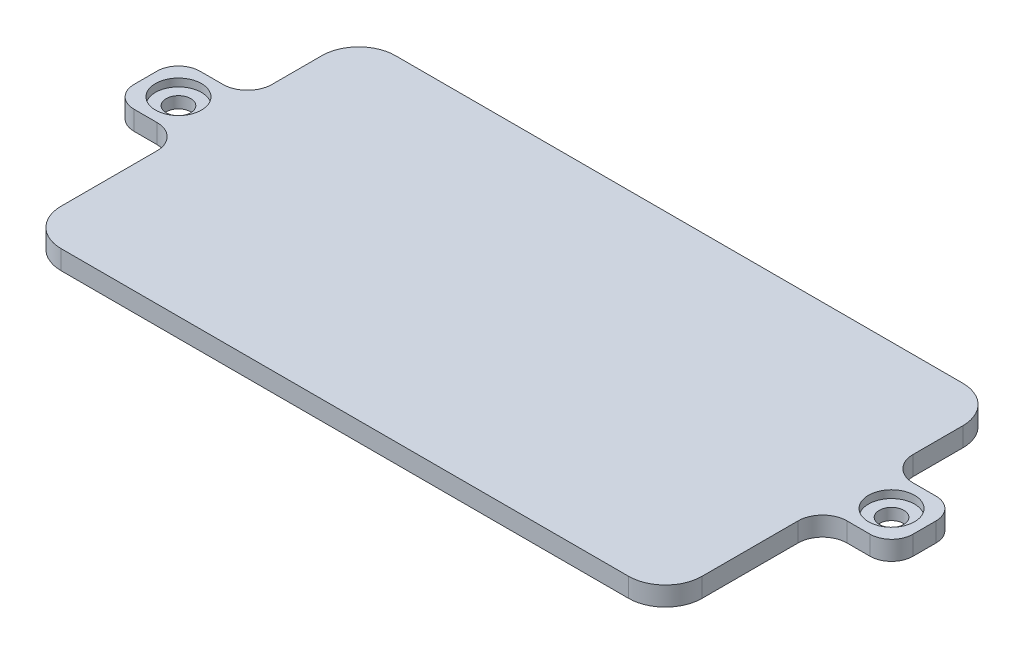
SolidWorks part; units mm, degrees
ref_plane "Front Plane" through (0, 0, 0) normal (0, 0, 1) x (1, 0, 0)
ref_plane "Top Plane" through (0, 0, 0) normal (0, 1, 0) x (1, 0, 0)
ref_plane "Right Plane" through (0, 0, 0) normal (1, 0, 0) x (0, 0, -1)
sketch "草图1" plane through (0, 0, 0) normal (0, 1, 0) x (1, 0, 0)
  line L14 (26.1354, 0.2) -> (100.1354, 0.2)
  line L15 (104.9354, 17.5) -> (104.9354, 5)
  line L16 (111.1354, 20.7) -> (108.1354, 20.7)
  line L17 (113.9354, 26.5) -> (113.9354, 23.5)
  line L18 (108.1354, 29.3) -> (111.1354, 29.3)
  line L19 (104.9354, 39) -> (104.9354, 32.5)
  line L20 (100.1354, 43.8) -> (26.1354, 43.8)
  line L21 (21.3354, 39) -> (21.3354, 32.5)
  line L22 (18.1354, 29.3) -> (15.1354, 29.3)
  line L23 (12.3354, 26.5) -> (12.3354, 23.5)
  line L24 (15.1354, 20.7) -> (18.1354, 20.7)
  line L25 (21.3354, 17.5) -> (21.3354, 5)
  arc A12 (100.1354, 0.2) -> (104.9354, 5) centre (100.1354, 5) ccw
  arc A13 (108.1354, 20.7) -> (104.9354, 17.5) centre (108.1354, 17.5) ccw
  arc A14 (113.9354, 23.5) -> (111.1354, 20.7) centre (111.1354, 23.5) cw
  arc A15 (111.1354, 29.3) -> (113.9354, 26.5) centre (111.1354, 26.5) cw
  arc A16 (104.9354, 32.5) -> (108.1354, 29.3) centre (108.1354, 32.5) ccw
  arc A17 (104.9354, 39) -> (100.1354, 43.8) centre (100.1354, 39) ccw
  arc A18 (26.1354, 43.8) -> (21.3354, 39) centre (26.1354, 39) ccw
  arc A19 (18.1354, 29.3) -> (21.3354, 32.5) centre (18.1354, 32.5) ccw
  arc A20 (12.3354, 26.5) -> (15.1354, 29.3) centre (15.1354, 26.5) cw
  arc A21 (15.1354, 20.7) -> (12.3354, 23.5) centre (15.1354, 23.5) cw
  arc A22 (18.1354, 20.7) -> (21.3354, 17.5) centre (18.1354, 17.5) cw
  arc A23 (26.1354, 0.2) -> (21.3354, 5) centre (26.1354, 5) cw
extrude "凸台-拉伸1" add sketch "草图1" along normal blind 2.5
sketch "草图2" plane through (0, 2.5, 0) normal (0, 1, 0) x (1, 0, 0)
  circle A0 centre (16.6354, 25) radius 1.6
  circle A1 centre (109.6354, 25) radius 1.6
extrude "切除-拉伸1" cut sketch "草图2" against normal through all
sketch "草图3" plane through (0, 2.5, 0) normal (0, 1, 0) x (1, 0, 0)
  circle A0 centre (16.6354, 25) radius 3
  circle A1 centre (109.6354, 25) radius 3
extrude "切除-拉伸2" cut sketch "草图3" against normal blind 1
